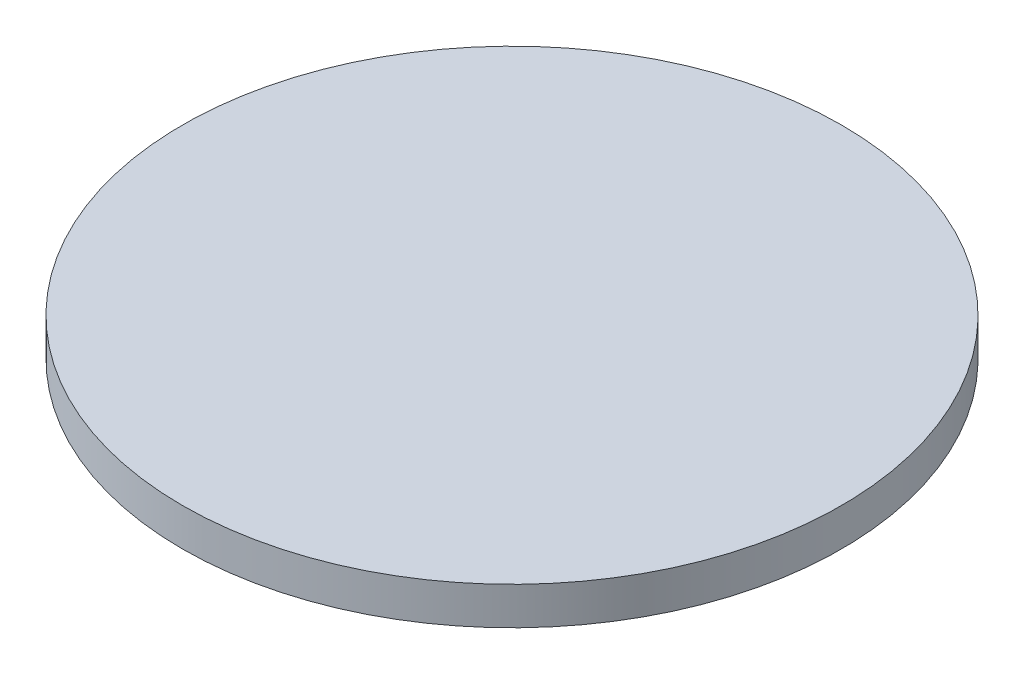
SolidWorks part; units mm, degrees
ref_plane "Front Plane" through (0, 0, 0) normal (0, 0, 1) x (1, 0, 0)
ref_plane "Top Plane" through (0, 0, 0) normal (0, 1, 0) x (1, 0, 0)
ref_plane "Right Plane" through (0, 0, 0) normal (1, 0, 0) x (0, 0, -1)
sketch "Sketch1" plane through (0, 0, 0) normal (0, 1, 0) x (1, 0, 0)
  circle A0 centre (0, 0) radius 87.5
  dimension "D1" = 175
extrude "Boss-Extrude1" add sketch "Sketch1" along normal blind 10
